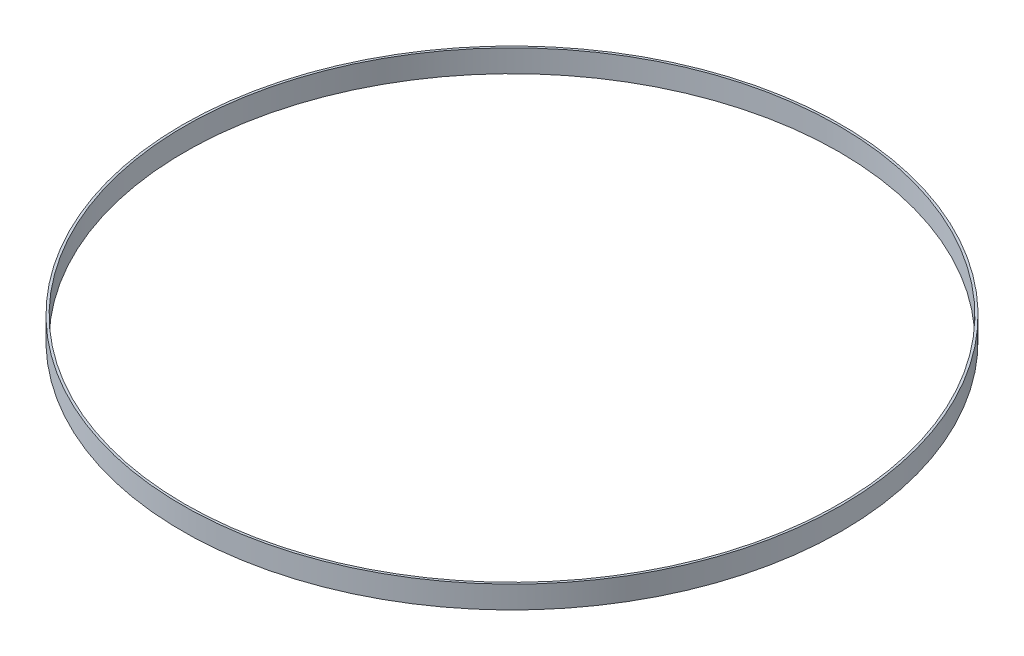
SolidWorks part; units mm, degrees
material "Copper"
ref_plane "Front Plane" through (0, 0, 0) normal (0, 0, 1) x (1, 0, 0)
ref_plane "Top Plane" through (0, 0, 0) normal (0, 1, 0) x (1, 0, 0)
ref_plane "Right Plane" through (0, 0, 0) normal (1, 0, 0) x (0, 0, -1)
sketch "Sketch1" plane through (0, 0, 0) normal (0, 1, 0) x (1, 0, 0)
  circle A0 centre (0, 0) radius 146.05
  dimension "D1" = 292.1
extrude "Extrude-Thin1" add sketch "Sketch1" along normal blind 10 thin
